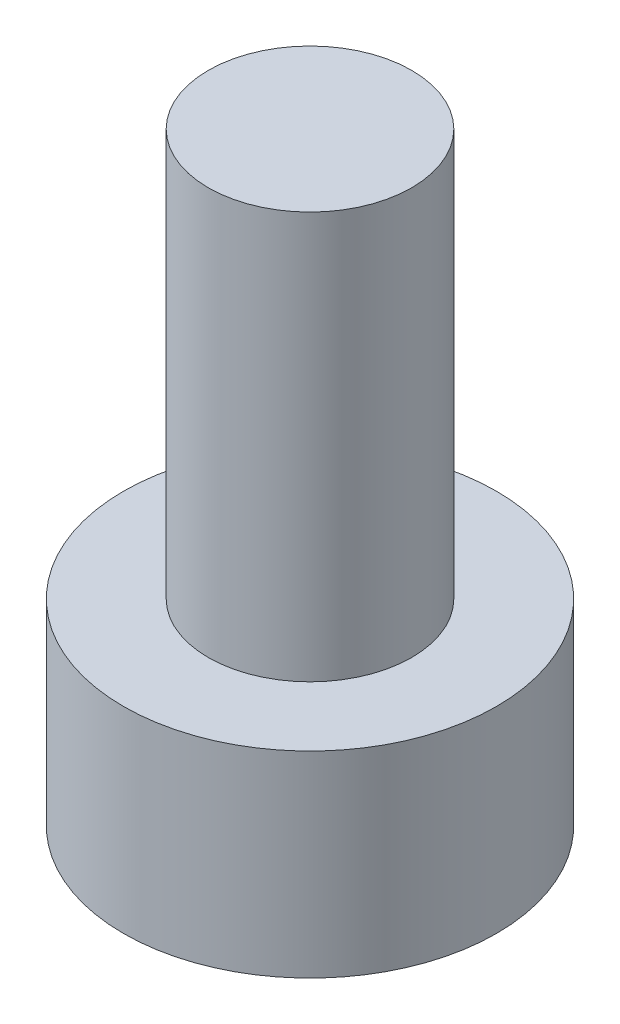
SolidWorks part; units mm, degrees
material "铸造碳钢"
ref_plane "前视基准面" through (0, 0, 0) normal (0, 0, 1) x (1, 0, 0)
ref_plane "上视基准面" through (0, 0, 0) normal (0, 1, 0) x (1, 0, 0)
ref_plane "右视基准面" through (0, 0, 0) normal (1, 0, 0) x (0, 0, -1)
other "Configuration Table"
sketch "草图1" plane through (0, 0, 0) normal (0, 1, 0) x (1, 0, 0)
  circle A0 centre (0, 0) radius 1.5
  dimension "D1" = 3
extrude "凸台-拉伸1" add sketch "草图1" along normal blind 6
sketch "草图2" plane through (0, 0, 0) normal (0, -1, 0) x (1, 0, 0)
  circle A0 centre (0, 0) radius 2.75
  dimension "D1" = 5.5
extrude "凸台-拉伸2" add sketch "草图2" along normal blind 2.9
sketch "草图3" plane through (0, -2.9, 0) normal (0, -1, 0) x (1, 0, 0)
  line L0 (0, 0) -> (0, 2.8092) construction
  line L1 (1.25, 0.7217) -> (0, 1.4434)
  line L2 (0, 1.4434) -> (-1.25, 0.7217)
  line L3 (-1.25, 0.7217) -> (-1.25, -0.7217)
  line L4 (-1.25, -0.7217) -> (0, -1.4434)
  line L5 (0, -1.4434) -> (1.25, -0.7217)
  line L6 (1.25, -0.7217) -> (1.25, 0.7217)
  circle A0 centre (0, 0) radius 1.25 construction
  dimension "D1" = 2.5
extrude "切除-拉伸1" cut sketch "草图3" against normal blind 1.5
